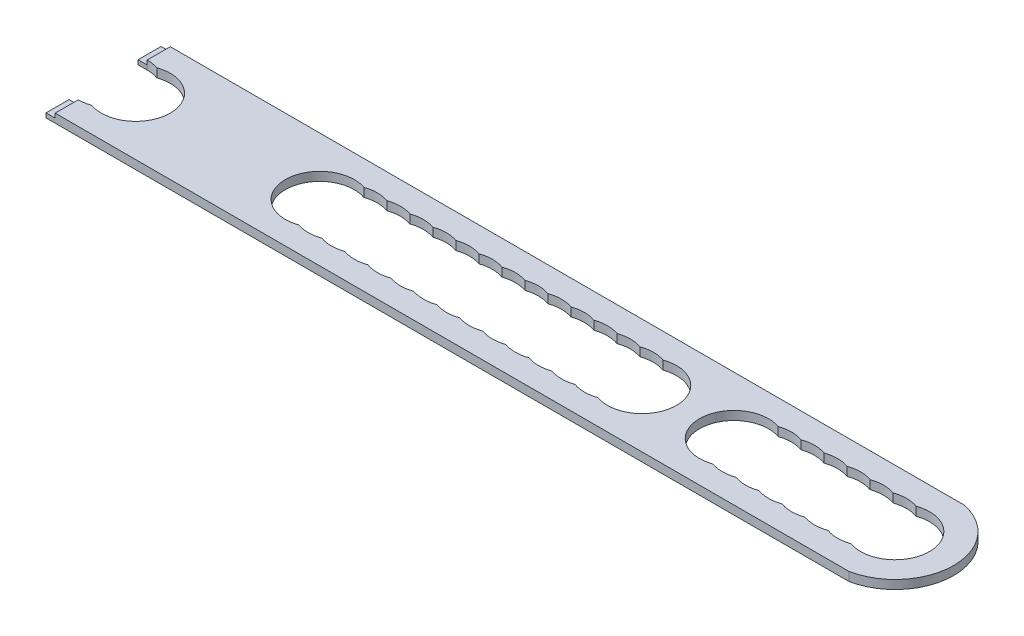
SolidWorks part; units mm, degrees
ref_plane "Front Plane" through (0, 0, 0) normal (0, 0, 1) x (1, 0, 0)
ref_plane "Top Plane" through (0, 0, 0) normal (0, 1, 0) x (1, 0, 0)
ref_plane "Right Plane" through (0, 0, 0) normal (1, 0, 0) x (0, 0, -1)
sketch "Sketch1" plane through (0, 0, 0) normal (0, 1, 0) x (1, 0, 0)
  line L0 (0, 12.5) -> (0, -12.5)
  line L1 (-172.5, -12.5) -> (172.5, -12.5)
  line L2 (-172.5, -12.5) -> (-172.5, 12.5)
  line L3 (-172.5, 12.5) -> (172.5, 12.5)
  line L4 (172.5, -12.5) -> (172.5, 12.5) construction
  line L5 (-172.5, -12.5) -> (172.5, 12.5) construction
  line L6 (-172.5, 12.5) -> (172.5, -12.5) construction
  line L7 (-172.5, 0) -> (172.5, 0) construction
  line L8 (41.25, 12.5) -> (41.25, -12.5) construction
  line L9 (123.75, 12.5) -> (123.75, -12.5) construction
  arc A0 (-2.5, 7.0711) -> (2.5, 7.0711) centre (0, 0) cw
  arc A1 (2.5, 7.0711) -> (7.5, 7.0711) centre (5, 0) cw
  arc A2 (7.5, 7.0711) -> (12.5, 7.0711) centre (10, 0) cw
  arc A3 (12.5, 7.0711) -> (17.5, 7.0711) centre (15, 0) cw
  arc A4 (17.5, 7.0711) -> (22.5, 7.0711) centre (20, 0) cw
  arc A5 (22.5, 7.0711) -> (27.5, 7.0711) centre (25, 0) cw
  arc A6 (27.5, 7.0711) -> (32.5, 7.0711) centre (30, 0) cw
  arc A7 (32.5, 7.0711) -> (37.5, 7.0711) centre (35, 0) cw
  arc A8 (37.5, 7.0711) -> (42.5, 7.0711) centre (40, 0) cw
  arc A9 (42.5, 7.0711) -> (47.5, 7.0711) centre (45, 0) cw
  arc A10 (47.5, 7.0711) -> (52.5, 7.0711) centre (50, 0) cw
  arc A11 (52.5, 7.0711) -> (57.5, 7.0711) centre (55, 0) cw
  arc A12 (57.5, 7.0711) -> (62.5, 7.0711) centre (60, 0) cw
  arc A13 (62.5, 7.0711) -> (67.5, 7.0711) centre (65, 0) cw
  arc A14 (67.5, 7.0711) -> (72.5, 7.0711) centre (70, 0) cw
  arc A15 (72.5, 7.0711) -> (77.5, 7.0711) centre (75, 0) cw
  arc A16 (77.5, 7.0711) -> (82.5, 7.0711) centre (80, 0) cw
  arc A17 (82.5, 7.0711) -> (87.5, 7.0711) centre (85, 0) cw
  arc A18 (87.5, 7.0711) -> (92.5, 7.0711) centre (90, 0) cw
  arc A19 (92.5, 7.0711) -> (97.5, 7.0711) centre (95, 0) cw
  arc A20 (97.5, 7.0711) -> (102.5, 7.0711) centre (100, 0) cw
  arc A21 (102.5, 7.0711) -> (107.5, 7.0711) centre (105, 0) cw
  arc A22 (107.5, 7.0711) -> (112.5, 7.0711) centre (110, 0) cw
  arc A23 (112.5, 7.0711) -> (117.5, 7.0711) centre (115, 0) cw
  arc A24 (117.5, 7.0711) -> (122.5, 7.0711) centre (120, 0) cw
  arc A25 (122.5, 7.0711) -> (127.5, 7.0711) centre (125, 0) cw
  arc A26 (127.5, 7.0711) -> (132.5, 7.0711) centre (130, 0) cw
  arc A27 (132.5, 7.0711) -> (137.5, 7.0711) centre (135, 0) cw
  arc A28 (137.5, 7.0711) -> (142.5, 7.0711) centre (140, 0) cw
  arc A29 (142.5, 7.0711) -> (147.5, 7.0711) centre (145, 0) cw
  arc A30 (147.5, 7.0711) -> (152.5, 7.0711) centre (150, 0) cw
  arc A31 (152.5, 7.0711) -> (157.5, 7.0711) centre (155, 0) cw
  arc A32 (157.5, 7.0711) -> (162.5, 7.0711) centre (160, 0) cw
  arc A33 (162.5, 7.0711) -> (167.5, 7.0711) centre (165, 0) cw
  arc A34 (167.5, 7.0711) -> (172.5, 7.0711) centre (170, 0) cw
  arc A35 (167.5, -7.0711) -> (172.5, -7.0711) centre (170, 0) ccw
  arc A36 (162.5, -7.0711) -> (167.5, -7.0711) centre (165, 0) ccw
  arc A37 (157.5, -7.0711) -> (162.5, -7.0711) centre (160, 0) ccw
  arc A38 (152.5, -7.0711) -> (157.5, -7.0711) centre (155, 0) ccw
  arc A39 (147.5, -7.0711) -> (152.5, -7.0711) centre (150, 0) ccw
  arc A40 (142.5, -7.0711) -> (147.5, -7.0711) centre (145, 0) ccw
  arc A41 (137.5, -7.0711) -> (142.5, -7.0711) centre (140, 0) ccw
  arc A42 (132.5, -7.0711) -> (137.5, -7.0711) centre (135, 0) ccw
  arc A43 (127.5, -7.0711) -> (132.5, -7.0711) centre (130, 0) ccw
  arc A44 (122.5, -7.0711) -> (127.5, -7.0711) centre (125, 0) ccw
  arc A45 (117.5, -7.0711) -> (122.5, -7.0711) centre (120, 0) ccw
  arc A46 (112.5, -7.0711) -> (117.5, -7.0711) centre (115, 0) ccw
  arc A47 (107.5, -7.0711) -> (112.5, -7.0711) centre (110, 0) ccw
  arc A48 (102.5, -7.0711) -> (107.5, -7.0711) centre (105, 0) ccw
  arc A49 (97.5, -7.0711) -> (102.5, -7.0711) centre (100, 0) ccw
  arc A50 (92.5, -7.0711) -> (97.5, -7.0711) centre (95, 0) ccw
  arc A51 (87.5, -7.0711) -> (92.5, -7.0711) centre (90, 0) ccw
  arc A52 (82.5, -7.0711) -> (87.5, -7.0711) centre (85, 0) ccw
  arc A53 (77.5, -7.0711) -> (82.5, -7.0711) centre (80, 0) ccw
  arc A54 (72.5, -7.0711) -> (77.5, -7.0711) centre (75, 0) ccw
  arc A55 (67.5, -7.0711) -> (72.5, -7.0711) centre (70, 0) ccw
  arc A56 (62.5, -7.0711) -> (67.5, -7.0711) centre (65, 0) ccw
  arc A57 (57.5, -7.0711) -> (62.5, -7.0711) centre (60, 0) ccw
  arc A58 (52.5, -7.0711) -> (57.5, -7.0711) centre (55, 0) ccw
  arc A59 (47.5, -7.0711) -> (52.5, -7.0711) centre (50, 0) ccw
  arc A60 (42.5, -7.0711) -> (47.5, -7.0711) centre (45, 0) ccw
  arc A61 (37.5, -7.0711) -> (42.5, -7.0711) centre (40, 0) ccw
  arc A62 (32.5, -7.0711) -> (37.5, -7.0711) centre (35, 0) ccw
  arc A63 (27.5, -7.0711) -> (32.5, -7.0711) centre (30, 0) ccw
  arc A64 (22.5, -7.0711) -> (27.5, -7.0711) centre (25, 0) ccw
  arc A65 (17.5, -7.0711) -> (22.5, -7.0711) centre (20, 0) ccw
  arc A66 (12.5, -7.0711) -> (17.5, -7.0711) centre (15, 0) ccw
  arc A67 (7.5, -7.0711) -> (12.5, -7.0711) centre (10, 0) ccw
  arc A68 (2.5, -7.0711) -> (7.5, -7.0711) centre (5, 0) ccw
  arc A69 (-2.5, -7.0711) -> (2.5, -7.0711) centre (0, 0) ccw
  arc A70 (172.5, 7.0711) -> (172.5, -7.0711) centre (170, 0) cw
  arc A71 (172.5, 12.5) -> (172.5, -12.5) centre (170, 0) cw
  arc A72 (7.5, 7.0711) -> (7.5, -7.0711) centre (5, 0) cw
  arc A73 (42.5, 7.0711) -> (42.5, -7.0711) centre (45, 0) ccw
  arc A74 (117.5, 7.0711) -> (117.5, -7.0711) centre (115, 0) cw
  arc A76 (132.5, 7.0711) -> (132.5, -7.0711) centre (135, 0) ccw
  point P0 (0, 0)
  dimension "D4" = 7.5
  dimension "D1" = 25
  dimension "D2" = 345
  dimension "D3" = 5
  dimension "D6" = 41.25
  dimension "D7" = 82.5
  dimension "D5" = 35
extrude "Boss-Extrude1" add sketch "Sketch1" along normal blind 1.9 contours A71 L3 L0 A0 A1 A2 A3 A4 A5 A6 A7 A8 A9 A10 A11 A12 A13 A14 A15 A16 A17 A18 A19 A20 A21 A22 A23 A24 A25 A26 A27 A28 A29 A30 A31 A32 A33 A34 A70 A35 A36 A37 A38 A39 A40 A41 A42 A43 A44 A45 A46 | A73 A8 A7 A6 A5 A4 A3 A2 A72 A67 A66 A65 A64 A63 A62 A61 | A76 A26 A25 A24 A74 A45 A44 A43
sketch "Sketch2" plane through (0, 0, 0) normal (0, 1, 0) x (1, 0, 0)
  line L1 (0, 12.5) -> (-2, 12.5)
  line L2 (0, 12.5) -> (0, 7.5)
  line L3 (0, 7.5) -> (-2, 7.5)
  line L4 (-2, 12.5) -> (-2, 7.5)
  line L5 (0, -7.5) -> (-2, -7.5)
  line L6 (0, -7.5) -> (0, -12.5)
  line L7 (0, -12.5) -> (-2, -12.5)
  line L8 (-2, -7.5) -> (-2, -12.5)
  point P5 (0, 0)
  dimension "D1" = 2
extrude "Boss-Extrude2" add sketch "Sketch2" along normal blind 0.95
equation "\"diameter_electrode_outer\"= 15mm"
equation "\"width_wing\"= 5mm"
equation "\"rad_curve\"= \"diameter_electrode_outer\" / 2"
equation "\"length_wing\"= 10mm"
equation "\"range_electrode_move_horizontal\"= ( \"length_wing\" / 2 ) * 66"
equation "\"length_slit_horizontal\"= \"diameter_electrode_outer\" + \"range_electrode_move_horizontal\""
equation "\"width_frame\"= \"diameter_electrode_outer\" + \"width_wing\" * 2"
equation "\"height_frame\" = 1.9mm"
equation "\"diameter_fluid_tank_outer\"= 40mm"
equation "\"range_electrode_move_vertical\"= 360mm"
equation "\"length_slit_vertical\"= \"range_electrode_move_vertical\" + \"diameter_electrode_outer\""
equation "\"width_frame_support\"= 10mm"
equation "\"D1@Fillet2\"=\"rad_curve\""
equation "\"D1@Sketch1\"=\"diameter_electrode_outer\"+\"width_wing\"*2"
equation "\"D2@Sketch1\"=\"length_slit_horizontal\""
equation "\"D3@Sketch1\"=\"length_wing\"/2"
equation "\"D4@Sketch1\"=\"rad_curve\""
equation "\"D6@Sketch1\"=\"range_electrode_move_horizontal\"/8"
equation "\"D7@Sketch1\"=\"range_electrode_move_horizontal\"/4"
equation "\"D1@Boss-Extrude1\"=\"height_frame\""
equation "\"width_connect\"= 2mm"
equation "\"height_connect\"= \"height_frame\" / 2"
equation "\"D1@Sketch2\"=\"width_connect\""
equation "\"D1@Boss-Extrude2\"=\"height_connect\""
